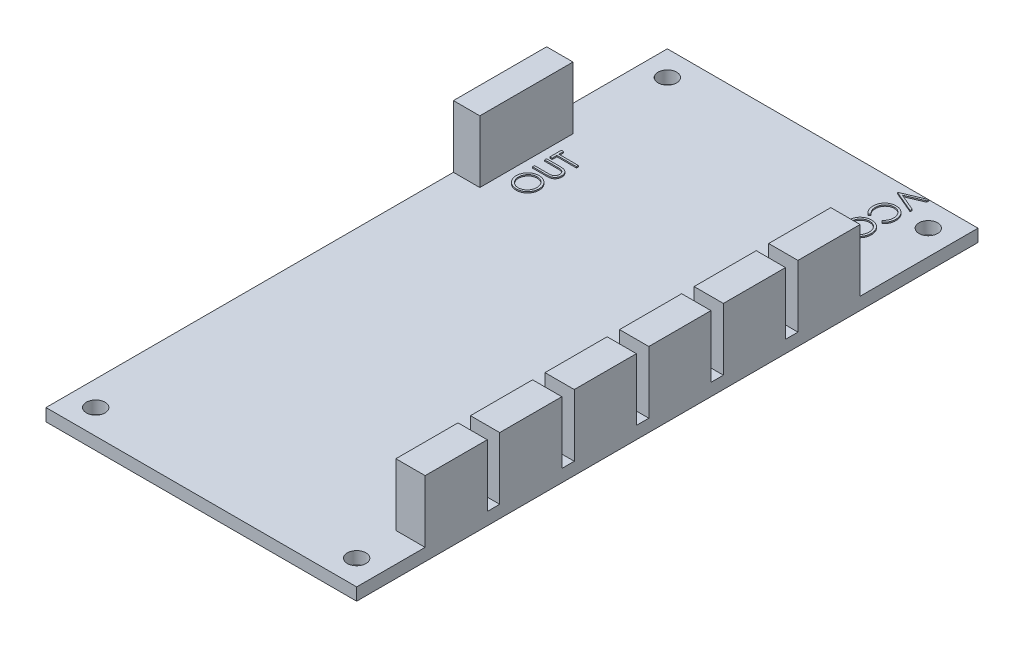
SolidWorks part; units mm, degrees
ref_plane "Ebene vorne" through (0, 0, 0) normal (0, 0, 1) x (1, 0, 0)
ref_plane "Ebene oben" through (0, 0, 0) normal (0, 1, 0) x (1, 0, 0)
ref_plane "Ebene rechts" through (0, 0, 0) normal (1, 0, 0) x (0, 0, -1)
sketch "Skizze1" plane through (0, 0, 0) normal (0, 1, 0) x (1, 0, 0)
  line L0 (0, 0) -> (0, -54812.6772) construction
  line L1 (0, 0) -> (54812.6772, 0) construction
  line L3 (-25, -50) -> (25, -50)
  line L4 (-25, -50) -> (-25, 50)
  line L5 (-25, 50) -> (25, 50)
  line L6 (25, -50) -> (25, 50)
  line L7 (-25, -50) -> (25, 50) construction
  line L8 (-25, 50) -> (25, -50) construction
  circle A0 centre (-21, -46) radius 1.5
  circle A1 centre (21, -46) radius 1.5
  circle A2 centre (-21, 46) radius 1.5
  circle A3 centre (21, 46) radius 1.5
  point P5 (0, 0)
  dimension "D3" = 42
  dimension "D4" = 3
  dimension "D1" = 50
  dimension "D2" = 100
  dimension "D5" = 4
extrude "Aufsatz-Linear austragen1" add sketch "Skizze1" along normal blind 2
sketch "Skizze2" plane through (0, 2, 0) normal (0, 1, 0) x (1, 0, 0)
  line L0 (-25, 50) -> (-25, -50) construction
  line L1 (-25, 30.5707) -> (-20.749, 30.5707)
  line L2 (-25, 30.5707) -> (-25, 15.5707)
  line L3 (-25, 15.5707) -> (-20.749, 15.5707)
  line L4 (-20.749, 30.5707) -> (-20.749, 15.5707)
  line L5 (25, -50) -> (25, 50) construction
  line L10 (25, 31.02) -> (20.2897, 31.02)
  line L11 (25, 31.02) -> (25, 21.02)
  line L12 (25, 21.02) -> (20.2897, 21.02)
  line L13 (20.2897, 31.02) -> (20.2897, 21.02)
  line L14 (25, 19.02) -> (20.2897, 19.02)
  line L15 (25, 19.02) -> (25, 9.02)
  line L16 (25, 9.02) -> (20.2897, 9.02)
  line L17 (20.2897, 19.02) -> (20.2897, 9.02)
  line L18 (25, 7.02) -> (20.2897, 7.02)
  line L19 (25, 7.02) -> (25, -2.98)
  line L20 (25, -2.98) -> (20.2897, -2.98)
  line L21 (20.2897, 7.02) -> (20.2897, -2.98)
  line L22 (25, -4.98) -> (20.2897, -4.98)
  line L23 (25, -4.98) -> (25, -14.98)
  line L24 (25, -14.98) -> (20.2897, -14.98)
  line L25 (20.2897, -4.98) -> (20.2897, -14.98)
  line L26 (25, -16.98) -> (20.2897, -16.98)
  line L27 (25, -16.98) -> (25, -26.98)
  line L28 (25, -26.98) -> (20.2897, -26.98)
  line L29 (20.2897, -16.98) -> (20.2897, -26.98)
  line L30 (25, -28.98) -> (20.2897, -28.98)
  line L31 (25, -28.98) -> (25, -38.98)
  line L32 (25, -38.98) -> (20.2897, -38.98)
  line L33 (20.2897, -28.98) -> (20.2897, -38.98)
  dimension "D1" = 15
  dimension "D3" = 10
  dimension "D4" = 6
extrude "Aufsatz-Linear austragen2" add sketch "Skizze2" along normal blind 10
sketch "Skizze3" plane through (0, 2, 0) normal (0, 1, 0) x (1, 0, 0)
  line L0 (13.7573, 50) -> (13.7573, 37.9395) construction
  line L1 (25, 50) -> (-25, 50) construction
  line L2 (13.7573, 31.4211) -> (13.7573, -40.1564) construction
  line L4 (-15.6918, 14.8346) -> (-15.6918, 30.2045) construction
  text T0 "VCC"
  text T1 "MEASUREMENT INPUTS"
  text T2 "OUT"
extrude "Aufsatz-Linear austragen3" add sketch "Skizze3" along normal blind 0.2
